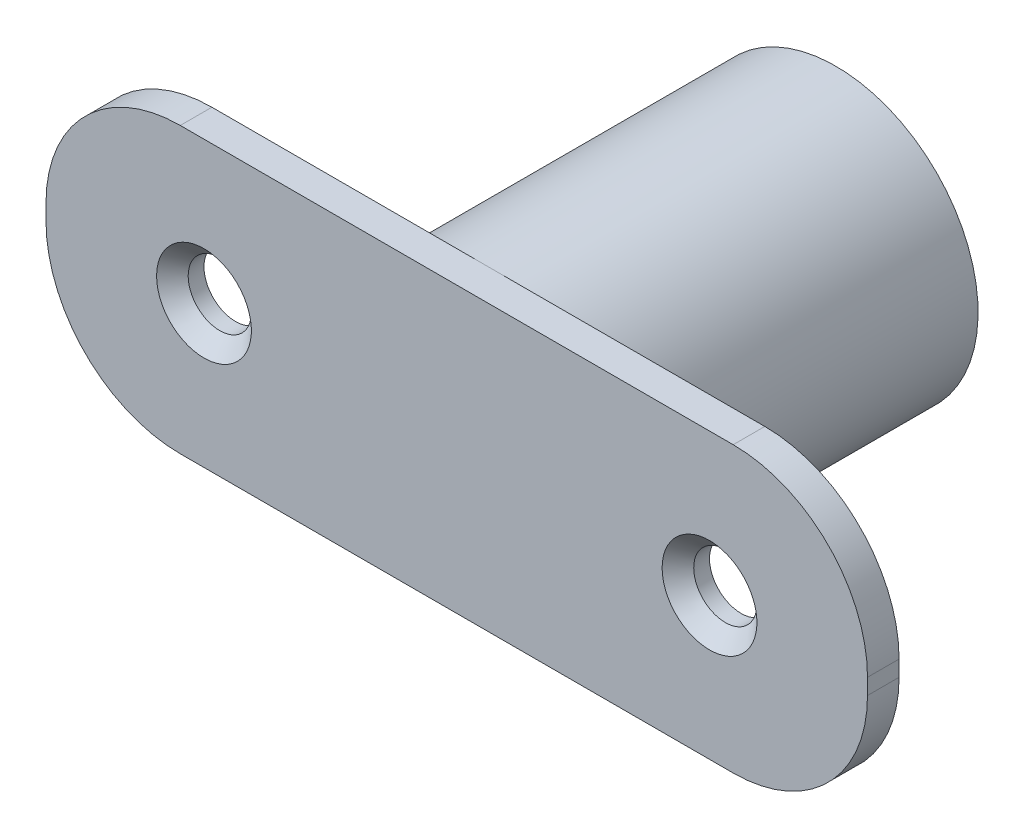
SolidWorks part; units mm, degrees
ref_plane "Plan de face" through (0, 0, 0) normal (0, 0, 1) x (1, 0, 0)
ref_plane "Plan de dessus" through (0, 0, 0) normal (0, 1, 0) x (1, 0, 0)
ref_plane "Plan de droite" through (0, 0, 0) normal (1, 0, 0) x (0, 0, -1)
sketch "Esquisse1" plane through (0, 0, 0) normal (0, 0, 1) x (1, 0, 0)
  line L1 (8.5, 0) -> (43.5, 0)
  line L2 (0, -8.5) -> (0, -9.5)
  line L3 (8.5, -18) -> (43.5, -18)
  line L4 (52, -8.5) -> (52, -9.5)
  circle A0 centre (10, -9) radius 2
  circle A1 centre (42, -9) radius 2
  arc A2 (52, -9.5) -> (43.5, -18) centre (43.5, -9.5) cw
  arc A3 (0, -9.5) -> (8.5, -18) centre (8.5, -9.5) ccw
  arc A4 (43.5, 0) -> (52, -8.5) centre (43.5, -8.5) cw
  arc A5 (0, -8.5) -> (8.5, 0) centre (8.5, -8.5) cw
  point P19 (0, 0)
  dimension "D1" = 4
  dimension "D2" = 4
  dimension "D8" = 8.5
  dimension "D3" = 32
  dimension "D4" = 18
  dimension "D5" = 9
  dimension "D6" = 10
  dimension "D7" = 10
extrude "Boss.-Extru.1" add sketch "Esquisse1" along normal blind 2
sketch "Esquisse2" plane through (0, 0, 0) normal (0, 0, -1) x (-1, 0, 0)
  line L0 (-26, -18) -> (-26, 0)
  line L1 (-8.5, -18) -> (-43.5, -18) construction
  line L2 (-43.5, 0) -> (-8.5, 0) construction
  line L3 (-52, -9) -> (0, -9)
  line L4 (-52, -9.5) -> (-52, -8.5) construction
  line L5 (0, -8.5) -> (0, -9.5) construction
  circle A0 centre (-26, -9) radius 9
  dimension "D1" = 18
extrude "Boss.-Extru.2" add sketch "Esquisse2" along normal blind 22 contours L3 A0 L0 | L0 A0 L3 | L3 A0 L0 | L0 A0 L3
chamfer "Chanfrein1" distance 1 angle 45 2 edges at (44, -9, 2) (12, -9, 2)
